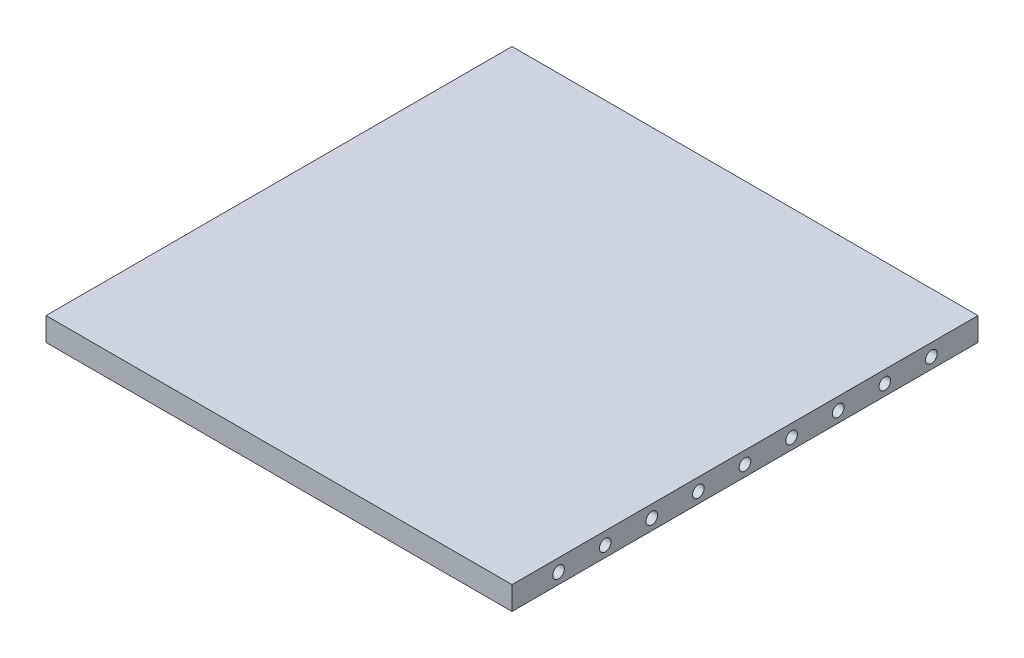
SolidWorks part; units mm, degrees
ref_plane "Front Plane" through (0, 0, 0) normal (0, 0, 1) x (1, 0, 0)
ref_plane "Top Plane" through (0, 0, 0) normal (0, 1, 0) x (1, 0, 0)
ref_plane "Right Plane" through (0, 0, 0) normal (1, 0, 0) x (0, 0, -1)
sketch "Sketch1" plane through (0, 0, 0) normal (0, 1, 0) x (1, 0, 0)
  line L1 (-63.5, -63.5) -> (63.5, -63.5)
  line L2 (-63.5, -63.5) -> (-63.5, 63.5)
  line L3 (-63.5, 63.5) -> (63.5, 63.5)
  line L4 (63.5, -63.5) -> (63.5, 63.5)
  line L5 (-63.5, -63.5) -> (63.5, 63.5) construction
  line L6 (-63.5, 63.5) -> (63.5, -63.5) construction
  point P0 (0, 0)
  dimension "D1" = 127
  dimension "D2" = 127
extrude "Boss-Extrude1" add sketch "Sketch1" along normal blind 6.35
sketch "Sketch3" plane through (-63.5, 0, 0) normal (-1, 0, 0) x (0, 0, 1)
  line L1 (-63.5, 6.35) -> (-63.5, 0) construction
  circle A0 centre (-50.8, 2.9738) radius 1.5875
  dimension "D1" = 12.7
  dimension "D2" = 3.175
extrude "Cut-Extrude1" cut sketch "Sketch3" against normal up to next
pattern_linear "LPattern1" count 9 spacing 12.7 along (0, 0, 1) of "Cut-Extrude1"
